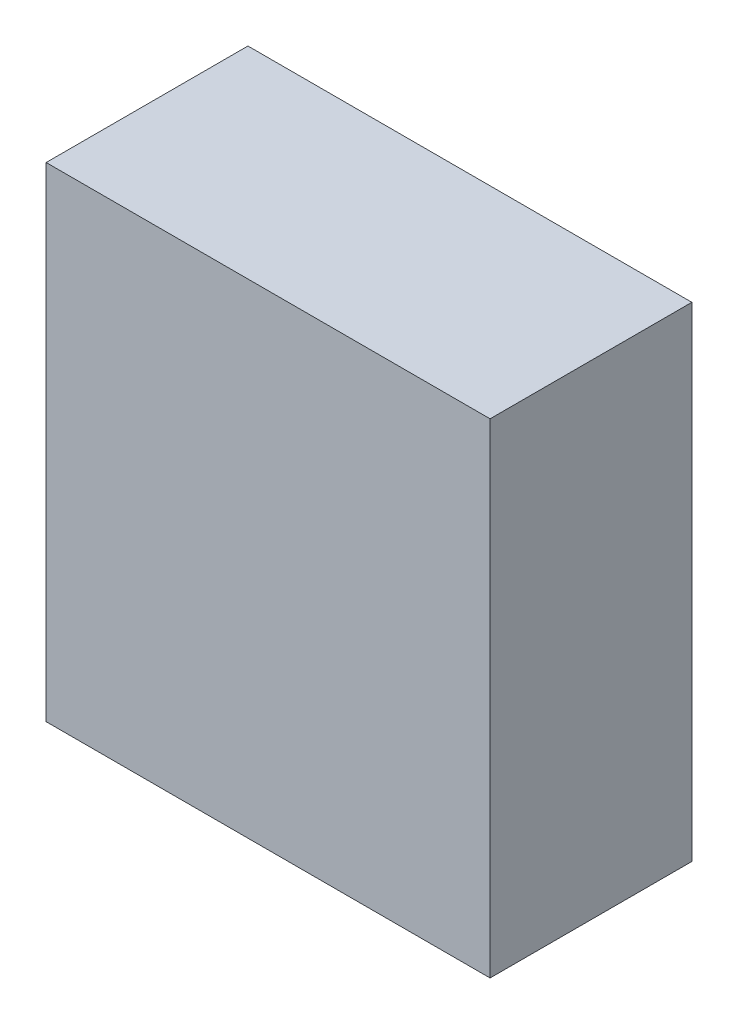
SolidWorks part; units mm, degrees
ref_plane "Front Plane" through (0, 0, 0) normal (1, 0, 0) x (0, 1, 0)
ref_plane "Top Plane" through (0, 0, 0) normal (0, 0, 1) x (0, 1, 0)
ref_plane "Right Plane" through (0, 0, 0) normal (0, 1, 0) x (-1, 0, 0)
sketch "Sketch1" plane through (0, 0, 0) normal (0, 0, 1) x (0, 1, 0)
  line L1 (-3.6, 3.3) -> (3.6, 3.3)
  line L2 (-3.6, 3.3) -> (-3.6, -3.3)
  line L3 (-3.6, -3.3) -> (3.6, -3.3)
  line L4 (3.6, 3.3) -> (3.6, -3.3)
  line L5 (-3.6, 3.3) -> (3.6, -3.3) construction
  line L6 (-3.6, -3.3) -> (3.6, 3.3) construction
  point P0 (0, 0)
  dimension "D1" = 7.2
  dimension "D2" = 6.6
extrude "Boss-Extrude1" add sketch "Sketch1" along normal blind 3 contours L4 L3 L2 L1
